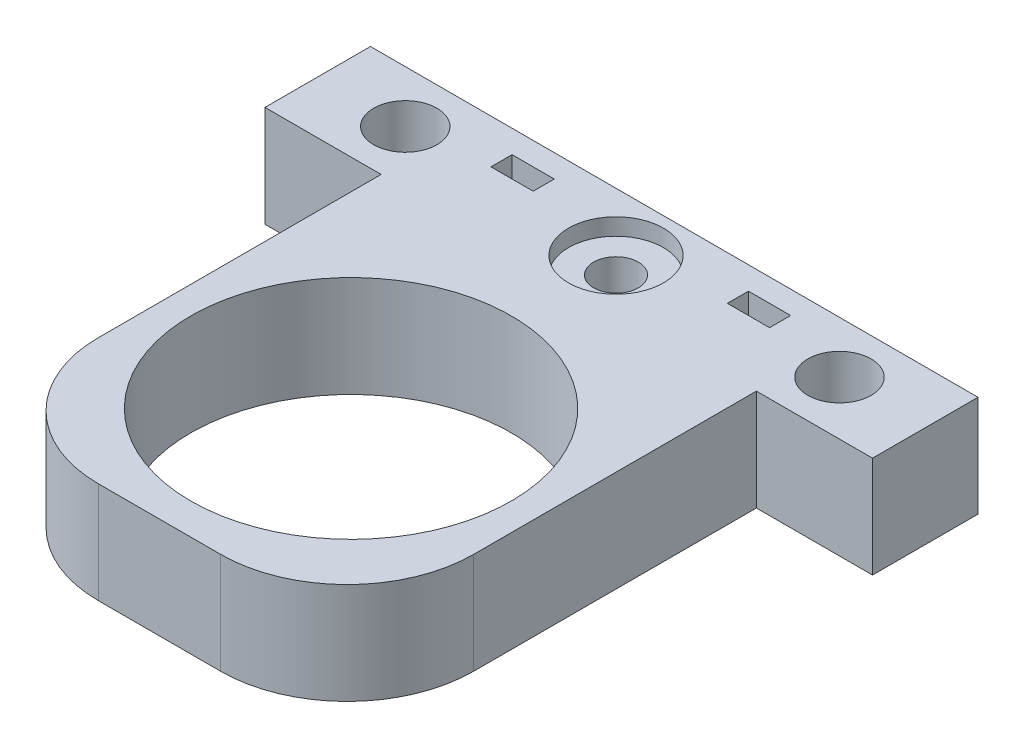
SolidWorks part; units mm, degrees
ref_plane "Front Plane" through (0, 0, 0) normal (0, 0, 1) x (1, 0, 0)
ref_plane "Top Plane" through (0, 0, 0) normal (0, 1, 0) x (1, 0, 0)
ref_plane "Right Plane" through (0, 0, 0) normal (1, 0, 0) x (0, 0, -1)
sketch "Sketch1" plane through (0, 0, 0) normal (0, 1, 0) x (1, 0, 0)
  line L0 (0, 0) -> (0, -45) construction
  line L1 (-65, 25) -> (65, 25)
  line L2 (-65, 25) -> (-65, -25)
  line L3 (-65, -25) -> (-32.8976, -25)
  line L4 (65, 25) -> (65, -25)
  line L5 (-65, 25) -> (65, -25) construction
  line L6 (-65, -25) -> (65, 25) construction
  line L7 (32.8976, -25) -> (65, -25)
  arc A0 (32.8976, -25) -> (-32.8976, -25) centre (0, -45) ccw
  point P0 (0, 0)
  dimension "D4" = 77
  dimension "D1" = 50
  dimension "D2" = 130
  dimension "D3" = 45
extrude "Boss-Extrude1" add sketch "Sketch1" along normal blind 60
sketch "Sketch2" plane through (0, 60, 0) normal (0, 1, 0) x (1, 0, 0)
  line L0 (0, -6.5) -> (0, 25) construction
  line L1 (65, 25) -> (-65, 25) construction
  circle A0 centre (-51.4526, 12.7142) radius 7.5
  arc A1 (32.8976, -25) -> (-32.8976, -25) centre (0, -45) ccw construction
  circle A2 centre (51.4526, 12.7142) radius 7.5
  dimension "D1" = 15
extrude "Cut-Extrude1" cut sketch "Sketch2" against normal blind 60
sketch "Sketch3" plane through (0, 60, 0) normal (0, 1, 0) x (1, 0, 0)
  line L0 (0, -6.5) -> (0, 25) construction
  line L1 (65, 25) -> (-65, 25) construction
  line L2 (-51.4526, 12.7142) -> (51.4526, 12.7142) construction
  arc A0 (32.8976, -25) -> (-32.8976, -25) centre (0, -45) ccw construction
  circle A1 centre (0, 12.7142) radius 5.25
  dimension "D1" = 10.5
extrude "Cut-Extrude2" cut sketch "Sketch3" against normal blind 60
sketch "Sketch4" plane through (0, 60, 0) normal (0, 1, 0) x (1, 0, 0)
  circle A0 centre (0, 12.7142) radius 11.5
  dimension "D1" = 23
extrude "Cut-Extrude3" cut sketch "Sketch4" against normal blind 4
sketch "Sketch5" plane through (0, 60, 0) normal (0, 1, 0) x (1, 0, 0)
  line L0 (0, 25) -> (0, -6.5) construction
  line L1 (-57.8842, -14.0803) -> (-47.8842, -14.0803)
  line L2 (-57.8842, -14.0803) -> (-57.8842, -19.0803)
  line L3 (-57.8842, -19.0803) -> (-47.8842, -19.0803)
  line L4 (-47.8842, -14.0803) -> (-47.8842, -19.0803)
  line L5 (65, 25) -> (-65, 25) construction
  line L6 (-33.0131, 19.5794) -> (-23.0131, 19.5794)
  line L7 (-33.0131, 19.5794) -> (-33.0131, 14.5794)
  line L8 (-33.0131, 14.5794) -> (-23.0131, 14.5794)
  line L9 (-23.0131, 19.5794) -> (-23.0131, 14.5794)
  line L10 (57.8842, -19.0803) -> (47.8842, -19.0803)
  line L11 (47.8842, -14.0803) -> (47.8842, -19.0803)
  line L12 (57.8842, -14.0803) -> (47.8842, -14.0803)
  line L13 (57.8842, -14.0803) -> (57.8842, -19.0803)
  line L14 (33.0131, 19.5794) -> (33.0131, 14.5794)
  line L15 (33.0131, 14.5794) -> (23.0131, 14.5794)
  line L16 (23.0131, 19.5794) -> (23.0131, 14.5794)
  line L17 (33.0131, 19.5794) -> (23.0131, 19.5794)
  arc A0 (32.8976, -25) -> (-32.8976, -25) centre (0, -45) ccw construction
  dimension "D1" = 5
  dimension "D2" = 10
extrude "Cut-Extrude4" cut sketch "Sketch5" against normal blind 60
sketch "Sketch6" plane through (0, 60, 0) normal (0, 1, 0) x (1, 0, 0)
  line L0 (-65, 25) -> (-65, -25) construction
  line L1 (-65, 0) -> (65, 0)
  line L2 (-65, 0) -> (-65, -90)
  line L3 (-65, -90) -> (65, -90)
  line L4 (65, 0) -> (65, -90)
  dimension "D1" = 90
extrude "Boss-Extrude2" add sketch "Sketch6" against normal blind 60
sketch "Sketch7" plane through (0, 60, 0) normal (0, 1, 0) x (1, 0, 0)
  line L0 (0, 12.7142) -> (0, -51.2858) construction
  circle A0 centre (0, -51.2858) radius 38.5
  dimension "D2" = 77
  dimension "D1" = 64
sketch "Sketch8" plane through (0, 0, 0) normal (0, -1, 0) x (1, 0, 0)
  line L1 (-65, 90) -> (65, 90)
  line L2 (-65, 90) -> (-65, -25)
  line L3 (-65, -25) -> (65, -25)
  line L4 (65, 90) -> (65, -25)
extrude "Cut-Extrude6" cut sketch "Sketch8" against normal blind 20
sketch "Sketch9" plane through (0, 60, 0) normal (0, 1, 0) x (1, 0, 0)
  line L0 (-65, 25) -> (-65, -90) construction
  line L1 (-65, 0) -> (-44.4744, 0)
  line L2 (-65, 0) -> (-65, -90)
  line L3 (-65, -90) -> (-44.4744, -90)
  line L4 (-44.4744, 0) -> (-44.4744, -90)
  line L5 (-65, -90) -> (65, -90) construction
  line L6 (0, 12.7142) -> (0, -90) construction
  line L7 (65, -90) -> (44.4744, -90)
  line L8 (44.4744, 0) -> (44.4744, -90)
  line L9 (65, 0) -> (44.4744, 0)
  line L10 (65, 0) -> (65, -90)
extrude "Cut-Extrude7" cut sketch "Sketch9" against normal blind 45
extrude "Cut-Extrude8" cut sketch "Sketch7" against normal blind 40
sketch "Sketch12" plane through (0, 0, 90) normal (0, 0, 1) x (1, 0, 0)
  line L1 (-44.4744, 60) -> (44.4744, 60)
  line L2 (-44.4744, 60) -> (-44.4744, 20)
  line L3 (-44.4744, 20) -> (44.4744, 20)
  line L4 (44.4744, 60) -> (44.4744, 20)
extrude "Boss-Extrude4" add sketch "Sketch12" along normal blind 7
sketch "Sketch13" plane through (65, 0, 0) normal (1, 0, 0) x (0, 0, -1)
  line L1 (0, 60) -> (25, 60)
  line L2 (0, 60) -> (0, 20)
  line L3 (0, 20) -> (25, 20)
  line L4 (25, 60) -> (25, 20)
extrude "Boss-Extrude5" add sketch "Sketch13" along normal blind 7
sketch "Sketch14" plane through (-65, 0, 0) normal (-1, 0, 0) x (0, 0, 1)
  line L1 (-25, 60) -> (0, 60)
  line L2 (-25, 60) -> (-25, 20)
  line L3 (-25, 20) -> (0, 20)
  line L4 (0, 60) -> (0, 20)
extrude "Boss-Extrude6" add sketch "Sketch14" along normal blind 7
sketch "Sketch16" plane through (0, 60, 0) normal (0, 1, 0) x (1, 0, 0)
  line L1 (-72, 25) -> (72.2963, 25)
  line L2 (-72, 25) -> (-72, -97.2488)
  line L3 (-72, -97.2488) -> (72.2963, -97.2488)
  line L4 (72.2963, 25) -> (72.2963, -97.2488)
extrude "Cut-Extrude9" cut sketch "Sketch16" against normal blind 16
sketch "Sketch23" plane through (0, 44, 0) normal (0, 1, 0) x (1, 0, 0)
  circle A2 centre (0, 12.7142) radius 10.5749
extrude "Boss-Extrude7" add sketch "Sketch23" against normal blind 24
sketch "Sketch24" plane through (0, 44, 0) normal (0, 1, 0) x (1, 0, 0)
  line L0 (0, 25) -> (0, 11.2) construction
  line L1 (72, 25) -> (-72, 25) construction
  circle A0 centre (0, 11.2) radius 5.3
  dimension "D2" = 10.6
  dimension "D1" = 13.8
extrude "Cut-Extrude11" cut sketch "Sketch24" against normal blind 24
sketch "Sketch25" plane through (0, 44, 0) normal (0, 1, 0) x (1, 0, 0)
  circle A1 centre (0, 11.2) radius 11.25
  dimension "D1" = 22.5
extrude "Cut-Extrude12" cut sketch "Sketch25" against normal blind 4
sketch "Sketch26" plane through (0, 44, 0) normal (0, 1, 0) x (1, 0, 0)
  line L0 (0, -12.7858) -> (0, -89.7858) construction
  circle A0 centre (0, -51.2858) radius 38.5 construction
  circle A1 centre (0, -51.2858) radius 41.2415
extrude "Boss-Extrude8" add sketch "Sketch26" against normal blind 24
sketch "Sketch27" plane through (0, 44, 0) normal (0, 1, 0) x (1, 0, 0)
  circle A0 centre (0, -51.5965) radius 38
  dimension "D1" = 76
extrude "Cut-Extrude13" cut sketch "Sketch27" against normal blind 24
fillet "Fillet2" radius 30 2 edges at (-44.4744, 32, 97) (44.4744, 32, 97)
